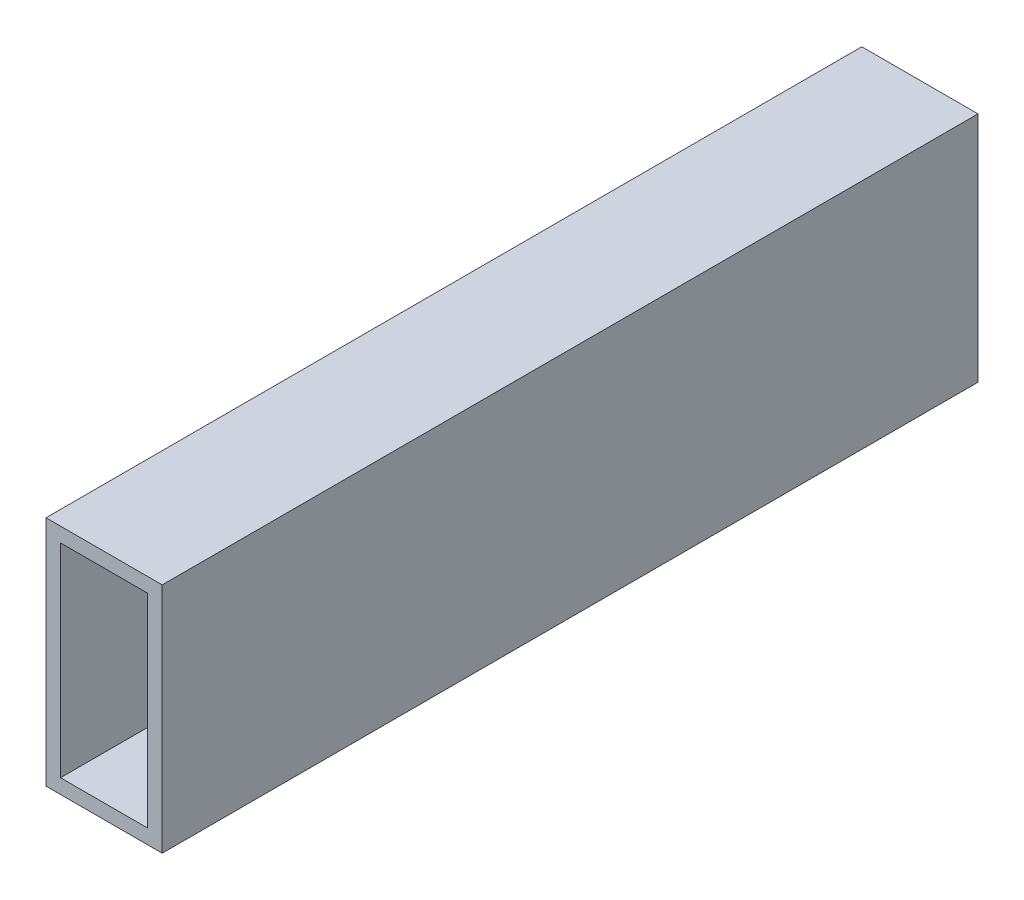
SolidWorks part; units mm, degrees
material "6061-T6 (SS)"
ref_plane "Front Plane" through (0, 0, 0) normal (0, 0, 1) x (1, 0, 0)
ref_plane "Top Plane" through (0, 0, 0) normal (0, 1, 0) x (1, 0, 0)
ref_plane "Right Plane" through (0, 0, 0) normal (1, 0, 0) x (0, 0, -1)
sketch "Sketch1" plane through (0, 0, 0) normal (0, 0, 1) x (1, 0, 0)
  line L1 (-12.7, -25.4) -> (12.7, -25.4)
  line L2 (-12.7, -25.4) -> (-12.7, 25.4)
  line L3 (-12.7, 25.4) -> (12.7, 25.4)
  line L4 (12.7, -25.4) -> (12.7, 25.4)
  line L5 (0, 25.4) -> (0, -25.4) construction
  line L6 (-12.7, 0) -> (12.7, 0) construction
  line L7 (-9.525, -22.225) -> (9.525, -22.225)
  line L8 (-9.525, -22.225) -> (-9.525, 22.225)
  line L9 (-9.525, 22.225) -> (9.525, 22.225)
  line L10 (9.525, -22.225) -> (9.525, 22.225)
  line L11 (0, 22.225) -> (0, -22.225) construction
  line L12 (-9.525, 0) -> (9.525, 0) construction
  point P0 (0, 0)
  point P4 (0, 0)
  dimension "D1" = 25.4
  dimension "D2" = 50.8
  dimension "D3" = 3.175
  dimension "D4" = 3.175
extrude "Boss-Extrude1" add sketch "Sketch1" along normal mid plane 178.308
